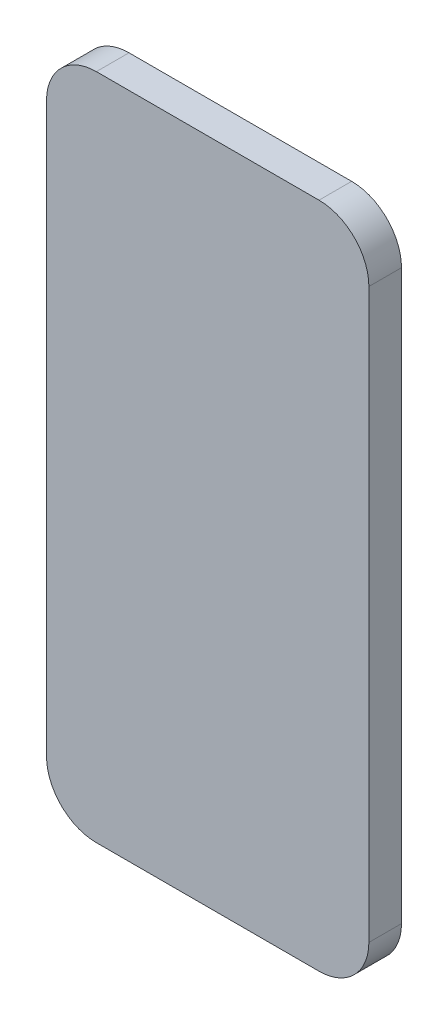
SolidWorks part; units mm, degrees
ref_plane "Front Plane" through (0, 0, 0) normal (0, 0, 1) x (1, 0, 0)
ref_plane "Top Plane" through (0, 0, 0) normal (0, 1, 0) x (1, 0, 0)
ref_plane "Right Plane" through (0, 0, 0) normal (1, 0, 0) x (0, 0, -1)
sketch "Sketch1" plane through (0, 0, 0) normal (0, 0, 1) x (1, 0, 0)
  line L1 (-40.766, 76.0174) -> (12.814, 76.0174)
  line L2 (-52.766, 64.0174) -> (-52.766, -72.6826)
  line L3 (-40.766, -84.6826) -> (12.814, -84.6826)
  line L4 (24.814, 64.0174) -> (24.814, -72.6826)
  line L5 (-52.766, 76.0174) -> (24.814, -84.6826) construction
  line L6 (-52.766, -84.6826) -> (24.814, 76.0174) construction
  arc A0 (12.814, -84.6826) -> (24.814, -72.6826) centre (12.814, -72.6826) ccw
  arc A1 (-52.766, -72.6826) -> (-40.766, -84.6826) centre (-40.766, -72.6826) ccw
  arc A2 (12.814, 76.0174) -> (24.814, 64.0174) centre (12.814, 64.0174) cw
  arc A3 (-40.766, 76.0174) -> (-52.766, 64.0174) centre (-40.766, 64.0174) ccw
  point P0 (-13.976, -4.3326)
  dimension "D3" = 12
  dimension "D1" = 160.7
  dimension "D2" = 77.58
extrude "Boss-Extrude1" add sketch "Sketch1" along normal blind 7.85
sketch "Sketch2" plane through (0, 0, 7.85) normal (0, 0, 1) x (1, 0, 0)
  line L1 (-40.7984, 63.3125) -> (-4.0684, 63.3125)
  line L2 (-40.7984, 63.3125) -> (-40.7984, 25.1025)
  line L3 (-40.7984, 25.1025) -> (-4.0684, 25.1025)
  line L4 (-4.0684, 63.3125) -> (-4.0684, 25.1025)
  line L5 (-40.7984, 63.3125) -> (-4.0684, 25.1025) construction
  line L6 (-40.7984, 25.1025) -> (-4.0684, 63.3125) construction
  point P0 (-22.4334, 44.2075)
  dimension "D1" = 36.73
  dimension "D2" = 38.21
